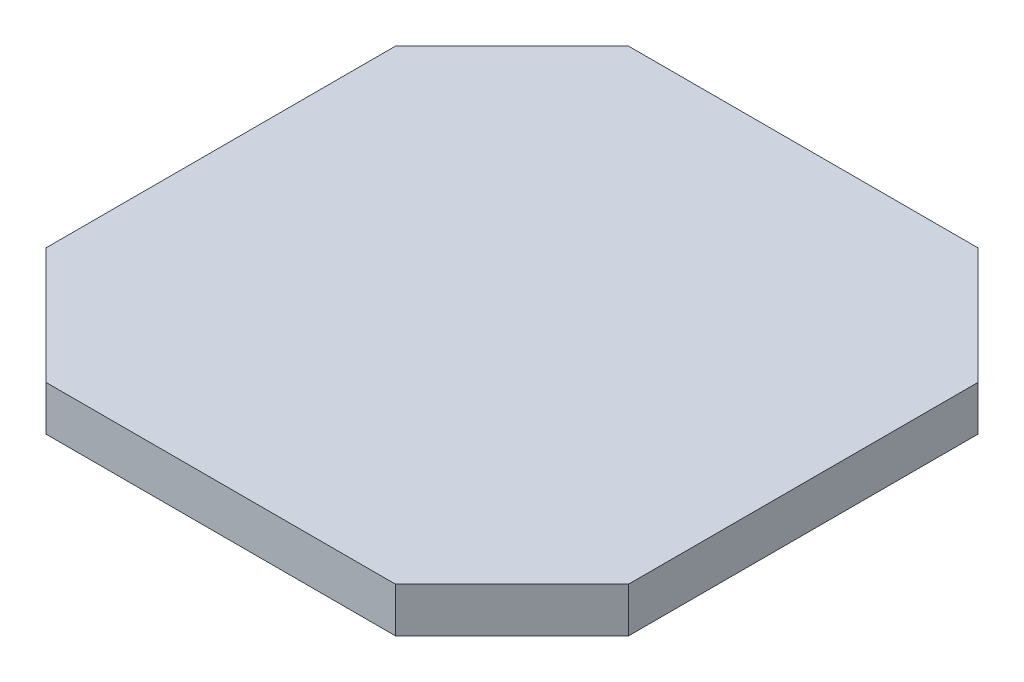
SolidWorks part; units mm, degrees
ref_plane "Front Plane" through (0, 0, 0) normal (0, 0, 1) x (1, 0, 0)
ref_plane "Top Plane" through (0, 0, 0) normal (0, 1, 0) x (1, 0, 0)
ref_plane "Right Plane" through (0, 0, 0) normal (1, 0, 0) x (0, 0, -1)
sketch "Sketch1" plane through (0, 0, 0) normal (0, 1, 0) x (1, 0, 0)
  line L0 (-65, 39) -> (-39, 65)
  line L1 (-39, 65) -> (39, 65)
  line L2 (39, 65) -> (65, 39)
  line L3 (65, 39) -> (65, -39)
  line L4 (65, -39) -> (39, -65)
  line L5 (39, -65) -> (-39, -65)
  line L6 (-39, -65) -> (-65, -39)
  line L7 (-65, -39) -> (-65, 39)
  line L16 (0, 171.9669) -> (0, -150.0475) construction
  line L17 (-185.3033, 0) -> (334.6917, 0) construction
  dimension "D1" = 130
  dimension "D2" = 130
  dimension "D3" = 78
  dimension "D4" = 78
  dimension "D5" = 78
  dimension "D6" = 78
extrude "Boss-Extrude1" add sketch "Sketch1" along normal blind 10
